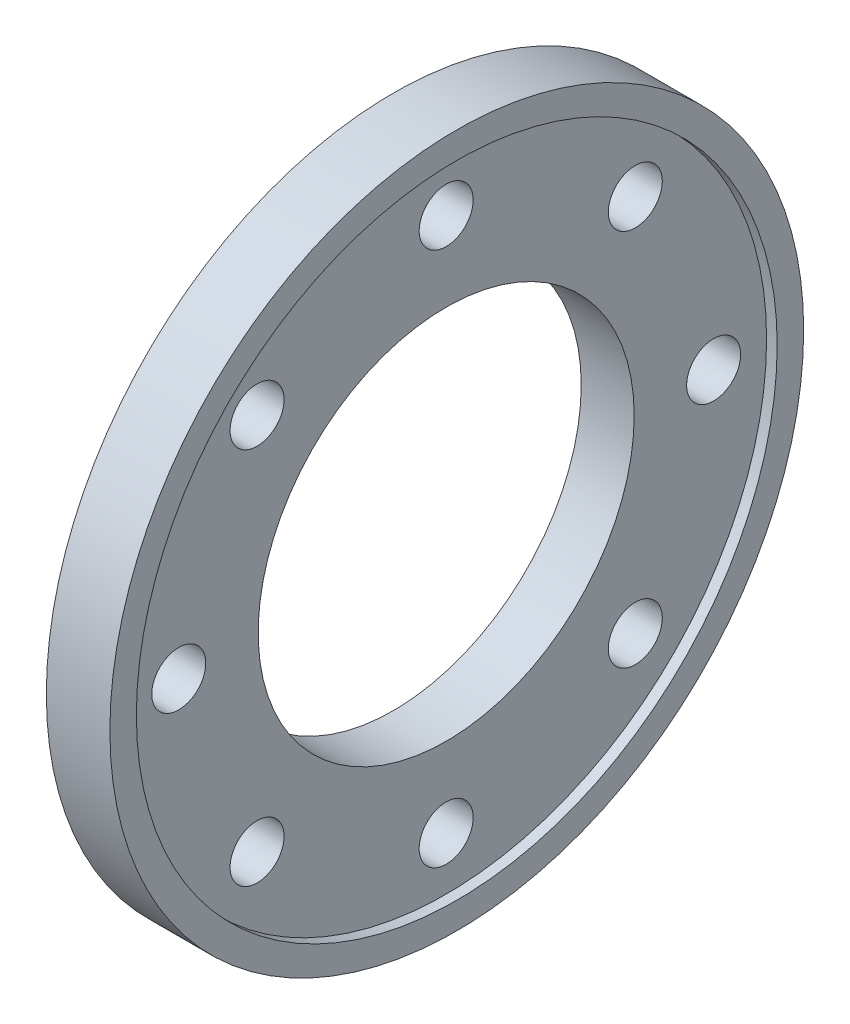
SolidWorks part; units mm, degrees
material "AISI 304"
ref_plane "Спереди" through (0, 0, 0) normal (0, 0, 1) x (1, 0, 0)
ref_plane "Сверху" through (0, 0, 0) normal (0, 1, 0) x (1, 0, 0)
ref_plane "Справа" through (0, 0, 0) normal (1, 0, 0) x (0, 0, -1)
other "Configuration Table"
sketch "Эскиз1" plane through (0, 0, 0) normal (1, 0, 0) x (0, 0, -1)
  line L0 (0, 0) -> (0, 50.5) construction
  circle A0 centre (0, 0) radius 35.5
  circle A1 centre (0, 0) radius 65.5
  circle A2 centre (0, 0) radius 50.5 construction
  circle A3 centre (0, 50.5) radius 5.1
  circle A4 centre (35.7089, 35.7089) radius 5.1
  circle A5 centre (50.5, 0) radius 5.1
  circle A6 centre (35.7089, -35.7089) radius 5.1
  circle A7 centre (0, -50.5) radius 5.1
  circle A8 centre (-35.7089, -35.7089) radius 5.1
  circle A9 centre (-50.5, 0) radius 5.1
  circle A10 centre (-35.7089, 35.7089) radius 5.1
  point P24 (0, 0)
  dimension "D1" = 71
  dimension "D4" = 10.2
  dimension "D2" = 15
  dimension "D3" = 15
  dimension "D5" = 8
extrude "Бобышка-Вытянуть1" add sketch "Эскиз1" along normal mid plane 12
sketch "Эскиз2" plane through (6, 0, 0) normal (1, 0, 0) x (0, 0, -1)
  circle A0 centre (0, 0) radius 65.5
  circle A1 centre (0, 0) radius 60.5
  dimension "D1" = 131
  dimension "D2" = 5
extrude "Вырез-Вытянуть1" cut sketch "Эскиз2" against normal blind 2 flip side to cut
equation "\"D3@Эскиз1\"=\"D2@Эскиз1\""
